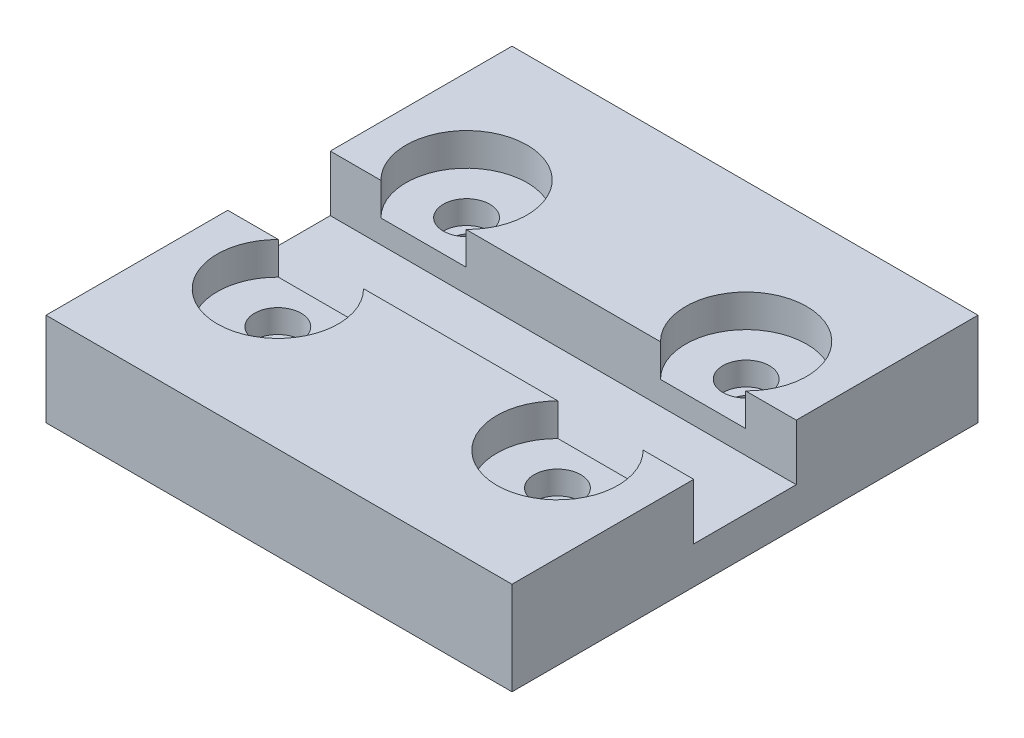
SolidWorks part; units mm, degrees
ref_plane "Front Plane" through (0, 0, 0) normal (0, 0, 1) x (1, 0, 0)
ref_plane "Top Plane" through (0, 0, 0) normal (0, 1, 0) x (1, 0, 0)
ref_plane "Right Plane" through (0, 0, 0) normal (1, 0, 0) x (0, 0, -1)
sketch "Sketch2" plane through (0, 0, 0) normal (0, 1, 0) x (1, 0, 0)
  line L1 (-87.6427, 8.4112) -> (12.3573, 8.4112)
  line L2 (-87.6427, 8.4112) -> (-87.6427, -91.5888)
  line L3 (-87.6427, -91.5888) -> (12.3573, -91.5888)
  line L4 (12.3573, 8.4112) -> (12.3573, -91.5888)
  dimension "D1" = 100
  dimension "D2" = 100
extrude "Boss-Extrude1" add sketch "Sketch2" along normal blind 20 contours L2 L1 L4 L3
sketch "Sketch3" plane through (0, 20, 0) normal (0, 1, 0) x (1, 0, 0)
  line L0 (12.3573, 8.4112) -> (12.3573, -91.5888) construction
  line L1 (12.3573, -31.5888) -> (-87.6427, -31.5888)
  line L2 (12.3573, -31.5888) -> (12.3573, -51.5888)
  line L3 (12.3573, -51.5888) -> (-87.6427, -51.5888)
  line L4 (-87.6427, -31.5888) -> (-87.6427, -51.5888)
  line L5 (-87.6427, 8.4112) -> (-87.6427, -91.5888) construction
  line L6 (-87.6427, -91.5888) -> (12.3573, -91.5888) construction
  line L7 (-87.6427, 8.4112) -> (12.3573, 8.4112) construction
  dimension "D1" = 40
  dimension "D2" = 40
sketch "Sketch4" plane through (0, 20, 0) normal (0, 1, 0) x (1, 0, 0)
extrude "Cut-Extrude1" cut sketch "Sketch3" against normal blind 12
sketch "Sketch5" plane through (0, 20, 0) normal (0, 1, 0) x (1, 0, 0)
  line L0 (12.3573, -51.5888) -> (12.3573, -91.5888) construction
  line L1 (-87.6427, -91.5888) -> (12.3573, -91.5888) construction
  circle A0 centre (-7.6427, -61.8388) radius 13
  dimension "D3" = 26
  dimension "D1" = 20
  dimension "D2" = 29.75
extrude "Cut-Extrude2" cut sketch "Sketch5" against normal blind 7
sketch "Sketch6" plane through (0, 20, 0) normal (0, 1, 0) x (1, 0, 0)
  line L0 (-87.6427, -51.5888) -> (-87.6427, -91.5888) construction
  line L1 (-87.6427, -91.5888) -> (12.3573, -91.5888) construction
  circle A0 centre (-67.6427, -61.8388) radius 13
  dimension "D3" = 26
  dimension "D1" = 20
  dimension "D2" = 29.75
extrude "Cut-Extrude3" cut sketch "Sketch6" against normal blind 7
sketch "Sketch7" plane through (0, 20, 0) normal (0, 1, 0) x (1, 0, 0)
  line L0 (-87.6427, 8.4112) -> (-87.6427, -31.5888) construction
  line L1 (-87.6427, 8.4112) -> (12.3573, 8.4112) construction
  circle A0 centre (-67.6427, -21.3388) radius 13
  dimension "D3" = 26
  dimension "D1" = 20
  dimension "D2" = 29.75
sketch "Sketch8" plane through (0, 20, 0) normal (0, 1, 0) x (1, 0, 0)
  line L0 (12.3573, 8.4112) -> (12.3573, -31.5888) construction
  line L1 (-87.6427, 8.4112) -> (12.3573, 8.4112) construction
  circle A0 centre (-7.6427, -21.3388) radius 13
  dimension "D3" = 26
  dimension "D1" = 20
  dimension "D2" = 29.75
extrude "Cut-Extrude5" cut sketch "Sketch8" against normal blind 7
extrude "Cut-Extrude10" cut sketch "Sketch7" against normal blind 7 contours A0
sketch "Sketch13" plane through (0, 13, 0) normal (0, 1, 0) x (1, 0, 0)
  circle A0 centre (-67.6427, -21.3388) radius 2.75
  arc A1 (-59.6466, -31.5888) -> (-75.6388, -31.5888) centre (-67.6427, -21.3388) ccw construction
  dimension "D1" = 5.5
extrude "Cut-Extrude11" cut sketch "Sketch13" against normal through all
sketch "Sketch14" plane through (0, 13, 0) normal (0, 1, 0) x (1, 0, 0)
  circle A0 centre (-7.6427, -21.3388) radius 2.75
  arc A1 (0.3534, -31.5888) -> (-15.6388, -31.5888) centre (-7.6427, -21.3388) ccw construction
  dimension "D1" = 5.5
extrude "Cut-Extrude12" cut sketch "Sketch14" against normal through all
sketch "Sketch15" plane through (0, 13, 0) normal (0, 1, 0) x (1, 0, 0)
  circle A0 centre (-7.6427, -61.8388) radius 2.75
  arc A1 (-15.6388, -51.5888) -> (0.3534, -51.5888) centre (-7.6427, -61.8388) ccw construction
  dimension "D1" = 5.5
extrude "Cut-Extrude13" cut sketch "Sketch15" against normal through all
sketch "Sketch16" plane through (0, 13, 0) normal (0, 1, 0) x (1, 0, 0)
  circle A0 centre (-67.6427, -61.8388) radius 2.75
  arc A1 (-75.6388, -51.5888) -> (-59.6466, -51.5888) centre (-67.6427, -61.8388) ccw construction
  dimension "D1" = 5.5
extrude "Cut-Extrude14" cut sketch "Sketch16" against normal through all contours A0
sketch "Sketch17" plane through (0, 0, 0) normal (0, -1, 0) x (-1, 0, 0)
  line L1 (7.6427, -26.2463) -> (11.8927, -23.7925)
  line L2 (11.8927, -23.7925) -> (11.8927, -18.8851)
  line L3 (11.8927, -18.8851) -> (7.6427, -16.4313)
  line L4 (7.6427, -16.4313) -> (3.3927, -18.8851)
  line L5 (3.3927, -18.8851) -> (3.3927, -23.7925)
  line L6 (3.3927, -23.7925) -> (7.6427, -26.2463)
  circle A0 centre (7.6427, -21.3388) radius 4.25 construction
  circle A1 centre (7.6427, -21.3388) radius 2.75 construction
  dimension "D1" = 8.5
extrude "Cut-Extrude15" cut sketch "Sketch17" against normal blind 5
sketch "Sketch19" plane through (0, 0, 0) normal (0, -1, 0) x (1, 0, 0)
  line L1 (-67.6427, 26.2463) -> (-71.8927, 23.7925)
  line L2 (-71.8927, 23.7925) -> (-71.8927, 18.8851)
  line L3 (-71.8927, 18.8851) -> (-67.6427, 16.4313)
  line L4 (-67.6427, 16.4313) -> (-63.3927, 18.8851)
  line L5 (-63.3927, 18.8851) -> (-63.3927, 23.7925)
  line L6 (-63.3927, 23.7925) -> (-67.6427, 26.2463)
  circle A0 centre (-67.6427, 21.3388) radius 4.25 construction
  circle A1 centre (-67.6427, 21.3388) radius 2.75 construction
  dimension "D1" = 8.5
extrude "Cut-Extrude16" cut sketch "Sketch19" against normal blind 5
sketch "Sketch20" plane through (0, 0, 0) normal (0, -1, 0) x (1, 0, 0)
  line L1 (-67.6427, 66.7463) -> (-71.8927, 64.2925)
  line L2 (-71.8927, 64.2925) -> (-71.8927, 59.3851)
  line L3 (-71.8927, 59.3851) -> (-67.6427, 56.9313)
  line L4 (-67.6427, 56.9313) -> (-63.3927, 59.3851)
  line L5 (-63.3927, 59.3851) -> (-63.3927, 64.2925)
  line L6 (-63.3927, 64.2925) -> (-67.6427, 66.7463)
  circle A0 centre (-67.6427, 61.8388) radius 4.25 construction
  circle A1 centre (-67.6427, 61.8388) radius 2.75 construction
  dimension "D1" = 8.5
extrude "Cut-Extrude17" cut sketch "Sketch20" against normal blind 5
sketch "Sketch21" plane through (0, 0, 0) normal (0, -1, 0) x (1, 0, 0)
  line L1 (-7.6427, 66.7463) -> (-11.8927, 64.2925)
  line L2 (-11.8927, 64.2925) -> (-11.8927, 59.3851)
  line L3 (-11.8927, 59.3851) -> (-7.6427, 56.9313)
  line L4 (-7.6427, 56.9313) -> (-3.3927, 59.3851)
  line L5 (-3.3927, 59.3851) -> (-3.3927, 64.2925)
  line L6 (-3.3927, 64.2925) -> (-7.6427, 66.7463)
  circle A0 centre (-7.6427, 61.8388) radius 4.25 construction
  circle A1 centre (-7.6427, 61.8388) radius 2.75 construction
  dimension "D1" = 8.5
extrude "Cut-Extrude18" cut sketch "Sketch21" against normal blind 5
sketch "Sketch22" plane through (0, 0, 31.5888) normal (0, 0, 1) x (1, 0, 0)
  line L1 (-87.6427, 8) -> (12.3573, 8)
  line L2 (-87.6427, 8) -> (-87.6427, 20)
  line L3 (-87.6427, 20) -> (12.3573, 20)
  line L4 (12.3573, 8) -> (12.3573, 20)
extrude "Cut-Extrude19" cut sketch "Sketch22" against normal blind 1
sketch "Sketch23" plane through (0, 0, 51.5888) normal (0, 0, -1) x (-1, 0, 0)
  line L1 (-12.3573, 8) -> (87.6427, 8)
  line L2 (-12.3573, 8) -> (-12.3573, 20)
  line L3 (-12.3573, 20) -> (87.6427, 20)
  line L4 (87.6427, 8) -> (87.6427, 20)
extrude "Cut-Extrude20" cut sketch "Sketch23" against normal blind 1
sketch "Sketch24" plane through (0, 13, 0) normal (0, 1, 0) x (1, 0, 0)
  circle A0 centre (-67.6427, -61.8388) radius 5
  arc A1 (-76.7771, -52.5888) -> (-58.5083, -52.5888) centre (-67.6427, -61.8388) ccw construction
  dimension "D1" = 10
extrude "Cut-Extrude21" cut sketch "Sketch24" against normal blind 5
sketch "Sketch25" plane through (0, 13, 0) normal (0, 1, 0) x (1, 0, 0)
  circle A0 centre (-7.6427, -61.8388) radius 5
  arc A1 (-16.7771, -52.5888) -> (1.4917, -52.5888) centre (-7.6427, -61.8388) ccw construction
  dimension "D1" = 10
extrude "Cut-Extrude22" cut sketch "Sketch25" against normal blind 5
sketch "Sketch26" plane through (0, 13, 0) normal (0, 1, 0) x (1, 0, 0)
  circle A0 centre (-7.6427, -21.3388) radius 5
  arc A1 (1.4917, -30.5888) -> (-16.7771, -30.5888) centre (-7.6427, -21.3388) ccw construction
  dimension "D1" = 10
extrude "Cut-Extrude23" cut sketch "Sketch26" against normal blind 5
sketch "Sketch27" plane through (0, 13, 0) normal (0, 1, 0) x (1, 0, 0)
  circle A0 centre (-67.6427, -21.3388) radius 5
  arc A1 (-58.5083, -30.5888) -> (-76.7771, -30.5888) centre (-67.6427, -21.3388) ccw construction
  dimension "D1" = 10
extrude "Cut-Extrude24" cut sketch "Sketch27" against normal blind 5
